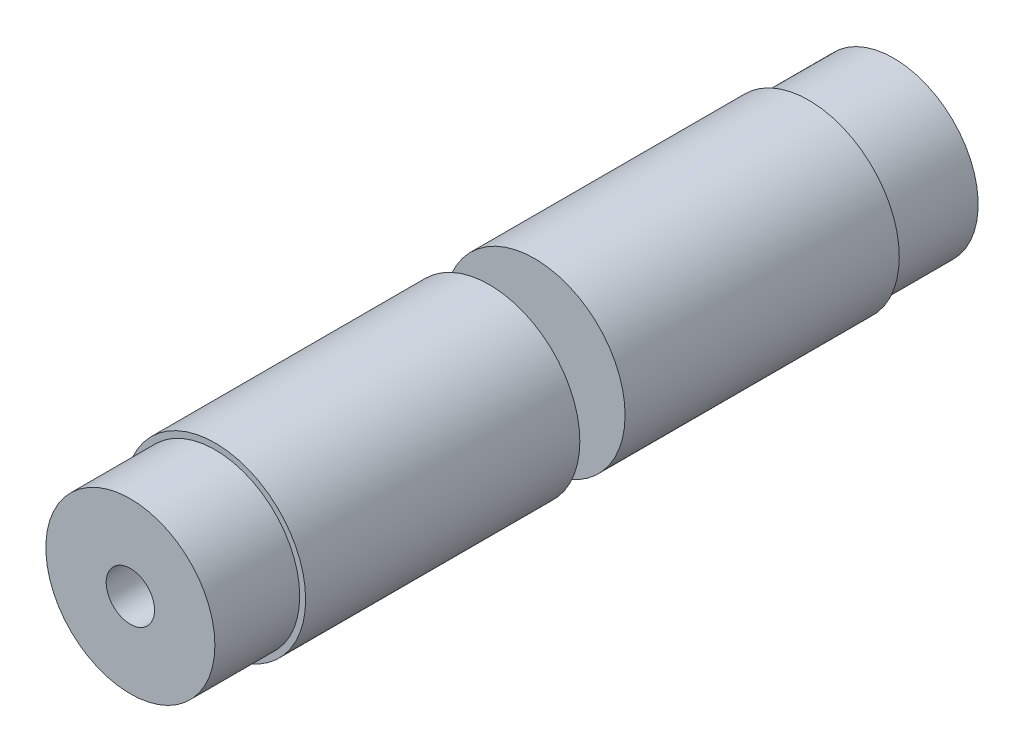
SolidWorks part; units mm, degrees
ref_plane "Front Plane" through (0, 0, 0) normal (0, 0, 1) x (1, 0, 0)
ref_plane "Top Plane" through (0, 0, 0) normal (0, 1, 0) x (1, 0, 0)
ref_plane "Right Plane" through (0, 0, 0) normal (1, 0, 0) x (0, 0, -1)
sketch "Sketch1" plane through (0, 0, 0) normal (0, 0, 1) x (1, 0, 0)
  circle A0 centre (0, 0) radius 4.275
  circle A1 centre (0, 0) radius 16
  dimension "D1" = 8.55
  dimension "D2" = 32
extrude "Boss-Extrude1" add sketch "Sketch1" along normal blind 105
sketch "Sketch2" plane through (0, 0, 105) normal (0, 0, 1) x (1, 0, 0)
  circle A0 centre (0, 0) radius 4.275
  circle A1 centre (0, 0) radius 14.95
  dimension "D1" = 29.9
extrude "Boss-Extrude2" add sketch "Sketch2" along normal blind 15
sketch "Sketch3" plane through (0, 0, 0) normal (0, 0, -1) x (-1, 0, 0)
  circle A0 centre (0, 0) radius 4.275
  circle A1 centre (0, 0) radius 14.95
  dimension "D1" = 29.9
extrude "Boss-Extrude3" add sketch "Sketch3" along normal blind 15
sketch "Sketch4" plane through (0, 0, 0) normal (0, 0, 1) x (1, 0, 0)
  circle A0 centre (0, 0) radius 16
extrude "Cut-Extrude1" cut sketch "Sketch4" along normal blind 8 from offset 48.5
